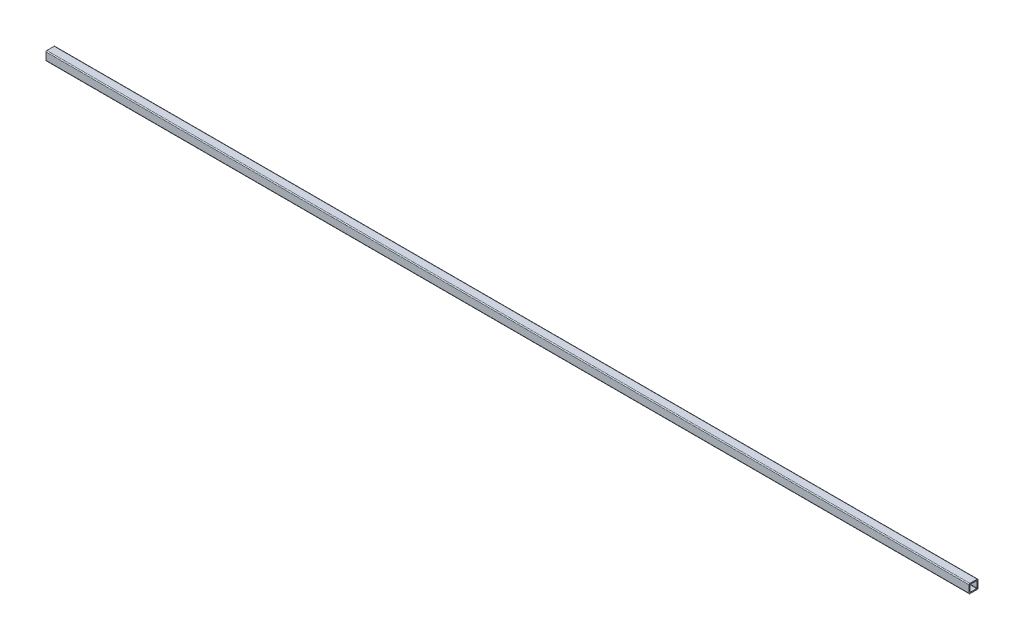
SolidWorks part; units mm, degrees
ref_plane "Front Plane" through (0, 0, 0) normal (0, 0, 1) x (1, 0, 0)
ref_plane "Top Plane" through (0, 0, 0) normal (0, 1, 0) x (1, 0, 0)
ref_plane "Right Plane" through (0, 0, 0) normal (1, 0, 0) x (0, 0, -1)
sketch "Sketch3" plane through (0, 0, 0) normal (1, 0, 0) x (0, 0, -1)
  line L1 (-12.7, 12.7) -> (12.7, 12.7)
  line L2 (-12.7, 12.7) -> (-12.7, -12.7)
  line L3 (-12.7, -12.7) -> (12.7, -12.7)
  line L4 (12.7, 12.7) -> (12.7, -12.7)
  line L5 (-12.7, 12.7) -> (12.7, -12.7) construction
  line L6 (-12.7, -12.7) -> (12.7, 12.7) construction
  line L7 (-9.652, -9.652) -> (9.652, -9.652)
  line L8 (-9.652, -9.652) -> (-9.652, 9.652)
  line L9 (-9.652, 9.652) -> (9.652, 9.652)
  line L10 (9.652, -9.652) -> (9.652, 9.652)
  line L11 (-9.652, -9.652) -> (9.652, 9.652) construction
  line L12 (-9.652, 9.652) -> (9.652, -9.652) construction
  point P0 (0, 0)
  point P6 (0, 0)
  dimension "D1" = 25.4
  dimension "D2" = 19.304
  dimension "D3" = 19.304
  dimension "D4" = 25.4
extrude "Boss-Extrude1" add sketch "Sketch3" against normal blind 2610
fillet "Fillet1" radius 2.5 4 edges at (-1305, -12.7, -12.7) (-1305, -12.7, 12.7) (-1305, 12.7, -12.7) (-1305, 12.7, 12.7)
fillet "Fillet2" radius 1 4 edges at (-1305, -9.652, -9.652) (-1305, 9.652, -9.652) (-1305, 9.652, 9.652) (-1305, -9.652, 9.652)
